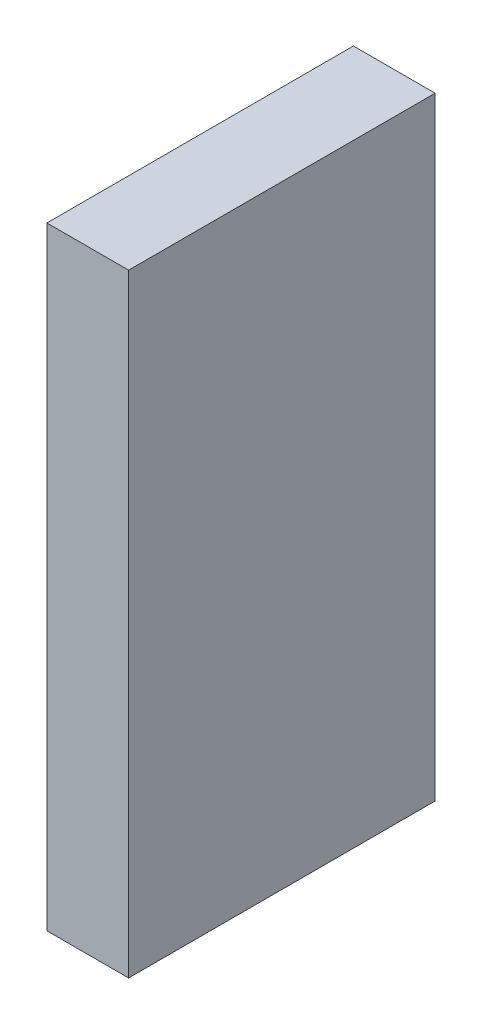
SolidWorks part; units mm, degrees
ref_plane "Front Plane" through (0, 0, 0) normal (0, 0, 1) x (1, 0, 0)
ref_plane "Top Plane" through (0, 0, 0) normal (0, 1, 0) x (1, 0, 0)
ref_plane "Right Plane" through (0, 0, 0) normal (1, 0, 0) x (0, 0, -1)
other "Configuration Table"
sketch "Sketch1" plane through (0, 0, 0) normal (0, 0, 1) x (1, 0, 0)
  line L1 (146, 700) -> (154, 700)
  line L2 (146, 700) -> (146, 760)
  line L3 (146, 760) -> (154, 760)
  line L4 (154, 700) -> (154, 760)
extrude "PACK_flap_parmagi_1_1" add sketch "Sketch1" against normal blind 30 from offset 185 separate body
